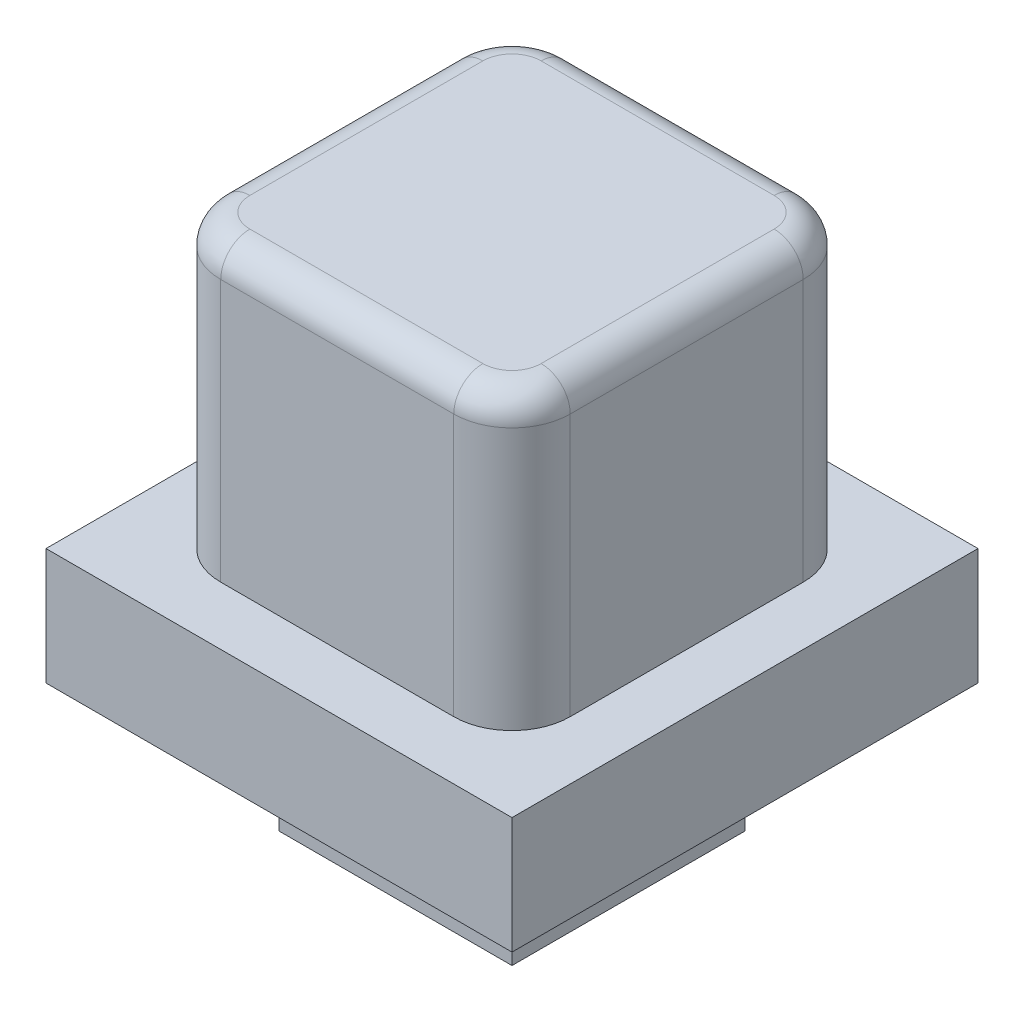
SolidWorks part; units mm, degrees
ref_plane "Front Plane" through (0, 0, 0) normal (0, 0, 1) x (1, 0, 0)
ref_plane "Top Plane" through (0, 0, 0) normal (0, 1, 0) x (1, 0, 0)
ref_plane "Right Plane" through (0, 0, 0) normal (1, 0, 0) x (0, 0, -1)
sketch "Sketch1" plane through (0, 0, 0) normal (0, 1, 0) x (1, 0, 0)
  line L1 (-4, -4) -> (4, -4)
  line L2 (-4, -4) -> (-4, 4)
  line L3 (-4, 4) -> (4, 4)
  line L4 (4, -4) -> (4, 4)
  line L5 (-4, -4) -> (4, 4) construction
  line L6 (-4, 4) -> (4, -4) construction
  point P0 (0, 0)
  dimension "D1" = 8
extrude "Boss-Extrude1" add sketch "Sketch1" along normal blind 2
sketch "Sketch2" plane through (0, 2, 0) normal (0, 1, 0) x (1, 0, 0)
  line L1 (-3, -3) -> (3, -3)
  line L2 (-3, -3) -> (-3, 3)
  line L3 (-3, 3) -> (3, 3)
  line L4 (3, -3) -> (3, 3)
  line L5 (-3, -3) -> (3, 3) construction
  line L6 (-3, 3) -> (3, -3) construction
  line L7 (-4, 4) -> (-4, -4) construction
  point P13 (-4, 0)
  point P14 (0, 0)
  dimension "D1" = 1
  dimension "D2" = 6
extrude "Boss-Extrude2" add sketch "Sketch2" along normal blind 5
fillet "Fillet1" radius 1 4 edges at (3, 4.5, 3) (3, 4.5, -3) (-3, 4.5, 3) (-3, 4.5, -3)
sketch "Sketch3" plane through (0, 0, 0) normal (0, -1, 0) x (-1, 0, 0)
  line L0 (-4, 4) -> (4, 4) construction
  line L1 (-2, -2) -> (2, -2)
  line L2 (-2, -2) -> (-2, 2)
  line L3 (-2, 2) -> (2, 2)
  line L4 (2, -2) -> (2, 2)
  line L5 (-2, -2) -> (2, 2) construction
  line L6 (-2, 2) -> (2, -2) construction
  point P0 (0, 0)
  dimension "D1" = 2
  dimension "D2" = 4
extrude "Boss-Extrude3" add sketch "Sketch3" along normal blind 2.2
fillet "Fillet2" radius 0.5 8 edges at (2.7071, 7, -2.7071) (3, 7, 0) (2.7071, 7, 2.7071) (0, 7, 3) (-2.7071, 7, 2.7071) (-3, 7, 0) (-2.7071, 7, -2.7071) (0, 7, -3)
